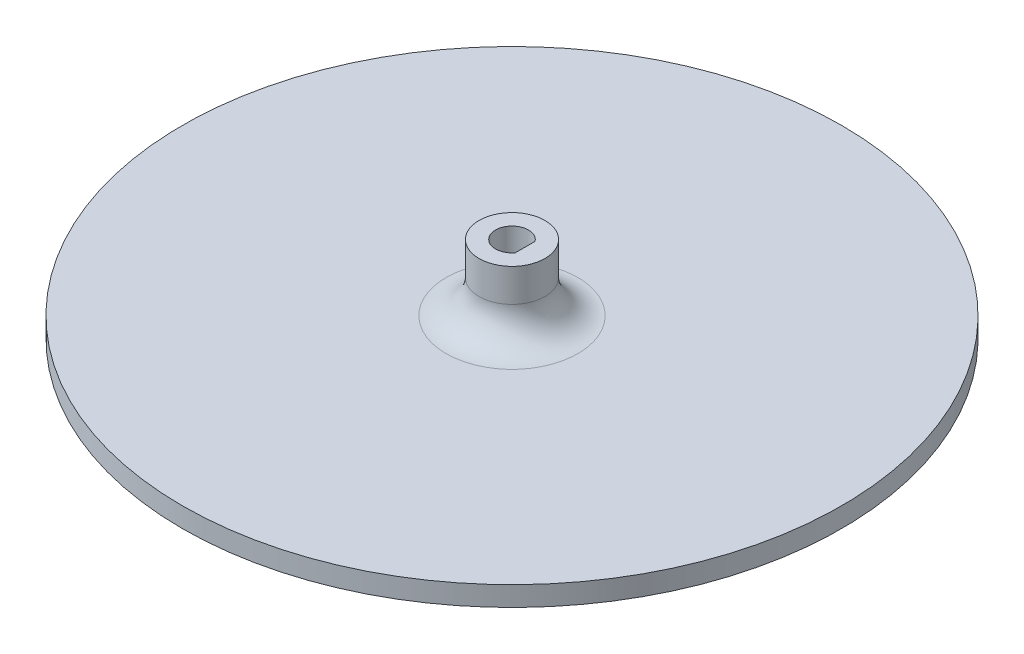
SolidWorks part; units mm, degrees
ref_plane "Front Plane" through (0, 0, 0) normal (0, 0, 1) x (1, 0, 0)
ref_plane "Top Plane" through (0, 0, 0) normal (0, 1, 0) x (1, 0, 0)
ref_plane "Right Plane" through (0, 0, 0) normal (1, 0, 0) x (0, 0, -1)
sketch "Sketch2" plane through (0, 0, 0) normal (0, 1, 0) x (1, 0, 0)
  circle A0 centre (0, 0) radius 50
  dimension "D1" = 100
extrude "Boss-Extrude1" add sketch "Sketch2" along normal blind 3
sketch "Sketch3" plane through (0, 3, 0) normal (0, 1, 0) x (1, 0, 0)
  line L0 (2, 1.5) -> (2, -1.5)
  circle A0 centre (0, 0) radius 5
  arc A1 (2, 1.5) -> (2, -1.5) centre (0, 0) ccw
  point P3 (-2.5, 0)
  dimension "D1" = 10
  dimension "D3" = 2.5
  dimension "D2" = 4.5
extrude "Boss-Extrude2" add sketch "Sketch3" along normal blind 10
fillet "Fillet1" radius 5 1 edges at (0, 3, 5)
